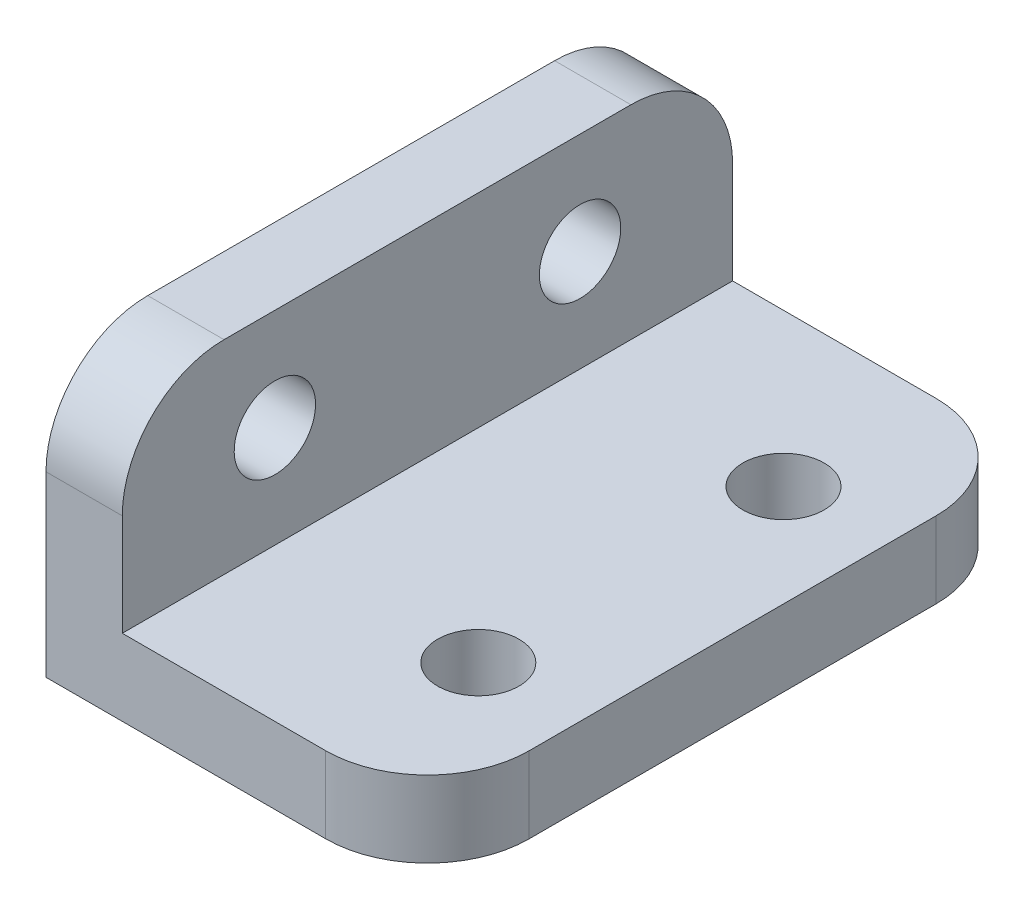
SolidWorks part; units mm, degrees
ref_plane "前视基准面" through (0, 0, 0) normal (0, 0, 1) x (1, 0, 0)
ref_plane "上视基准面" through (0, 0, 0) normal (0, 1, 0) x (1, 0, 0)
ref_plane "右视基准面" through (0, 0, 0) normal (1, 0, 0) x (0, 0, -1)
sketch "草图1" plane through (0, 0, 0) normal (0, 0, 1) x (1, 0, 0)
  line L0 (3, 231.6916) -> (3, 101.6916) construction
  line L1 (3, 112.6916) -> (6, 112.6916)
  line L2 (3, 112.6916) -> (3, -64.3846)
  line L4 (6, 112.6916) -> (6, 104.6916)
  line L6 (3, 101.6916) -> (18, 101.6916)
  line L7 (3, 101.6916) -> (3, -61.5122)
  line L8 (6, 104.6916) -> (18, 104.6916)
  line L9 (18, 101.6916) -> (18, 104.6916)
  dimension "D1" = 3
  dimension "D2" = 3
  dimension "D3" = 8
  dimension "D4" = 12
extrude "凸台-拉伸1" add sketch "草图1" against normal blind 24 contours L6 L9 L8 L4 L1 L2 L7
sketch "草图2" plane through (6, 0, 0) normal (1, 0, 0) x (0, 0, -1)
  line L0 (24, 112.6916) -> (0, 112.6916) construction
  line L1 (0, 112.6916) -> (0, 104.6916) construction
  line L2 (24, 112.6916) -> (24, 104.6916) construction
  circle A0 centre (6, 108.6916) radius 1.6
  circle A1 centre (18, 108.6916) radius 1.6
  dimension "D1" = 3.2
  dimension "D2" = 3.2
  dimension "D3" = 4
  dimension "D4" = 6
  dimension "D5" = 6
  dimension "D6" = 4
extrude "切除-拉伸1" cut sketch "草图2" against normal blind 24
sketch "草图3" plane through (0, 104.6916, 0) normal (0, 1, 0) x (1, 0, 0)
  line L0 (18, 24) -> (18, 0) construction
  line L1 (6, 0) -> (18, 0) construction
  line L2 (6, 24) -> (18, 24) construction
  circle A0 centre (14, 6) radius 1.6
  circle A1 centre (14, 18) radius 1.6
  dimension "D1" = 3.2
  dimension "D2" = 3.2
  dimension "D3" = 4
  dimension "D4" = 4
  dimension "D5" = 6
  dimension "D6" = 6
extrude "切除-拉伸2" cut sketch "草图3" against normal blind 24
fillet "圆角1" radius 4 4 edges at (18, 103.1916, -24) (18, 103.1916, 0) (4.5, 112.6916, -24) (4.5, 112.6916, 0)
